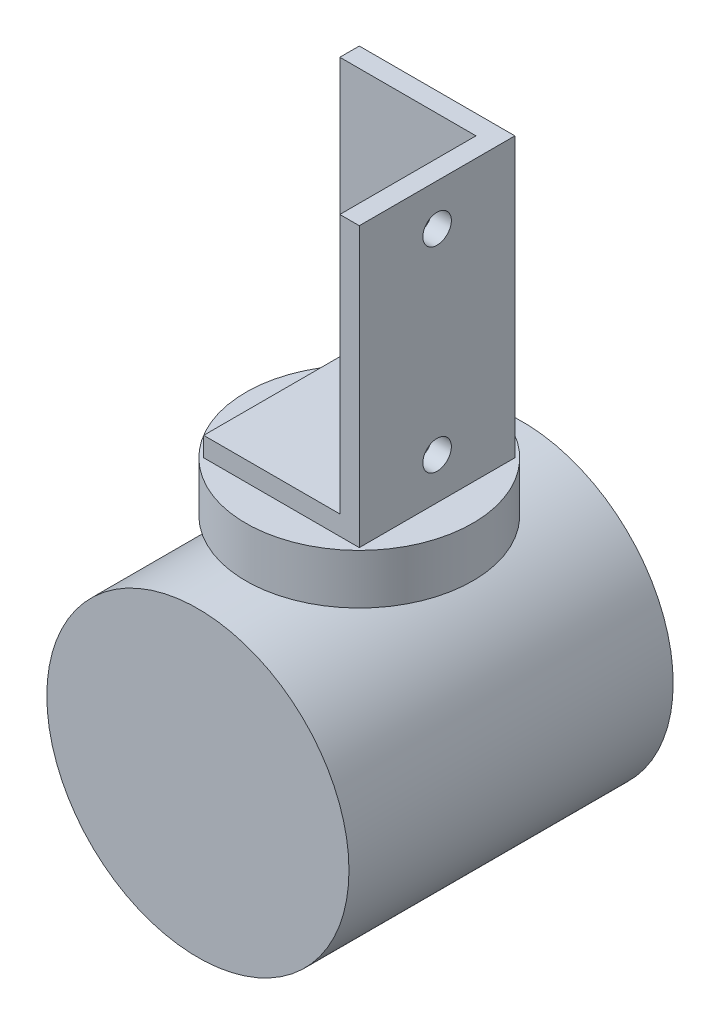
SolidWorks part; units mm, degrees
ref_plane "Front Plane" through (0, 0, 0) normal (0, 0, 1) x (1, 0, 0)
ref_plane "Top Plane" through (0, 0, 0) normal (0, 1, 0) x (1, 0, 0)
ref_plane "Right Plane" through (0, 0, 0) normal (1, 0, 0) x (0, 0, -1)
sketch "Sketch1" plane through (0, 0, 0) normal (0, 1, 0) x (1, 0, 0)
  line L1 (-15.24, 15.24) -> (15.24, 15.24)
  line L2 (-15.24, 15.24) -> (-15.24, -15.24)
  line L3 (-15.24, -15.24) -> (15.24, -15.24)
  line L4 (15.24, 15.24) -> (15.24, -15.24)
  line L5 (-15.24, 15.24) -> (15.24, -15.24) construction
  line L6 (-15.24, -15.24) -> (15.24, 15.24) construction
  point P0 (0, 0)
  dimension "D1" = 30.48
  dimension "D2" = 30.48
extrude "Boss-Extrude1" add sketch "Sketch1" along normal blind 3.81
sketch "Sketch2" plane through (0, 3.81, 0) normal (0, 1, 0) x (1, 0, 0)
  line L0 (15.24, -15.24) -> (15.24, 15.24) construction
  line L1 (-15.24, 15.24) -> (11.43, 15.24)
  line L2 (-15.24, 15.24) -> (-15.24, 11.43)
  line L3 (-15.24, 11.43) -> (11.43, 11.43)
  line L4 (11.43, 15.24) -> (15.24, 15.24)
  line L5 (-15.24, -15.24) -> (15.24, -15.24) construction
  line L6 (15.24, 15.24) -> (15.24, 11.43)
  line L7 (15.24, 11.43) -> (15.24, -15.24)
  line L8 (15.24, -15.24) -> (11.43, -15.24)
  line L9 (11.43, 11.43) -> (11.43, -15.24)
  dimension "D1" = 3.81
  dimension "D2" = 3.81
extrude "Boss-Extrude2" add sketch "Sketch2" along normal blind 50.8
sketch "Sketch3" plane through (15.24, 0, 0) normal (1, 0, 0) x (0, 0, -1)
  line L0 (-15.24, 0) -> (15.24, 0) construction
  line L1 (-15.24, 54.61) -> (15.24, 54.61) construction
  circle A0 centre (0, 46.482) radius 2.794
  circle A1 centre (0, 8.128) radius 2.794
  dimension "D1" = 5.588
  dimension "D2" = 5.588
  dimension "D3" = 8.128
  dimension "D4" = 8.128
extrude "Cut-Extrude1" cut sketch "Sketch3" against normal up to surface (3.81 mm away) up to face at (11.43, 35.56, -1.4287)
sketch "Sketch4" plane through (0, 0, 0) normal (0, -1, 0) x (1, 0, 0)
  circle A0 centre (0, 0) radius 22.225
  dimension "D1" = 44.45
extrude "Boss-Extrude3" add sketch "Sketch4" along normal blind 9.779
ref_plane "Plane1" through (0, 0, 0) normal (-1, 0, 0) x (0, 0, 1)
sketch "Sketch5" plane through (0, 0, 0) normal (-1, 0, 0) x (0, 0, 1)
  line L0 (-22.225, -9.779) -> (22.225, -9.779) construction
  line L1 (-31.8905, -39.37) -> (31.6095, -39.37)
  line L2 (-31.8905, -39.37) -> (-31.8905, -9.779)
  line L3 (-31.8905, -9.779) -> (31.6095, -9.779)
  line L4 (31.6095, -39.37) -> (31.6095, -9.779)
  line L5 (-31.8905, -39.37) -> (31.6095, -9.779) construction
  line L6 (-31.8905, -9.779) -> (31.6095, -39.37) construction
  point P0 (-0.1405, -24.5745)
  dimension "D1" = 29.591
  dimension "D2" = 0
  dimension "D3" = 63.5
revolve "Revolve1" add sketch "Sketch5" angle 360 about L1
